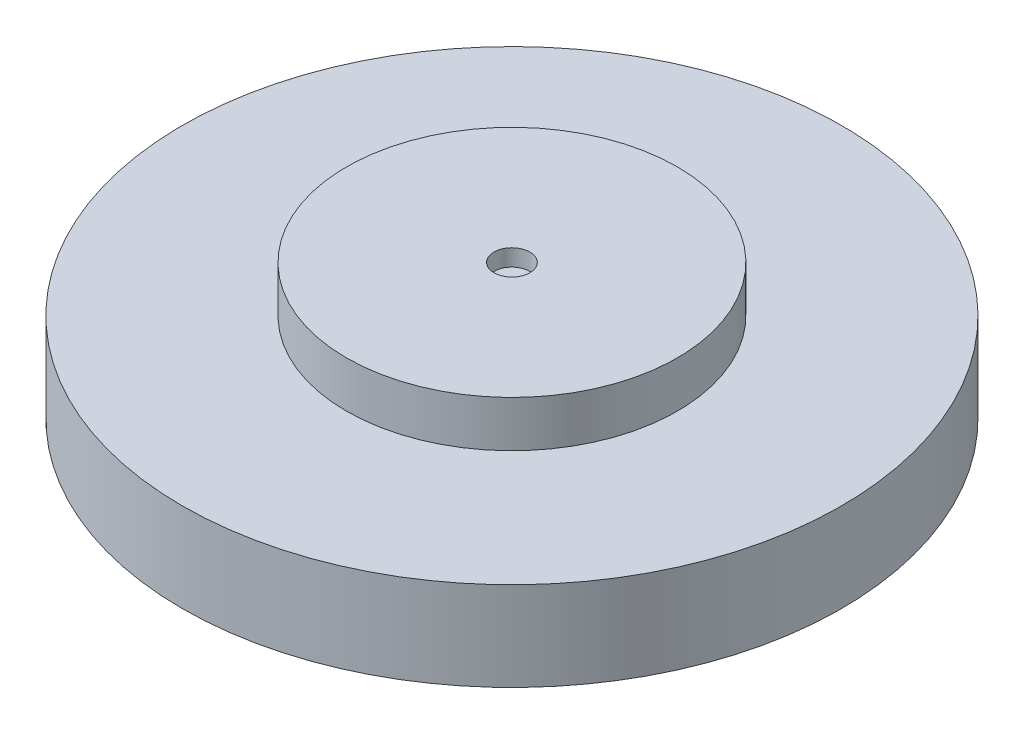
SolidWorks part; units mm, degrees
ref_plane "Front Plane" through (0, 0, 0) normal (0, 0, 1) x (1, 0, 0)
ref_plane "Top Plane" through (0, 0, 0) normal (0, 1, 0) x (1, 0, 0)
ref_plane "Right Plane" through (0, 0, 0) normal (1, 0, 0) x (0, 0, -1)
sketch "Sketch2" plane through (0, 0, 0) normal (0, 1, 0) x (1, 0, 0)
  circle A0 centre (0, 0) radius 50
  dimension "D1" = 100
extrude "Boss-Extrude1" add sketch "Sketch2" along normal blind 13.5
sketch "Sketch3" plane through (0, 13.5, 0) normal (0, 1, 0) x (1, 0, 0)
  circle A0 centre (0, 0) radius 25.1
  dimension "D1" = 50.2
extrude "Boss-Extrude2" add sketch "Sketch3" along normal blind 7
sketch "Sketch4" plane through (0, 20.5, 0) normal (0, 1, 0) x (1, 0, 0)
  circle A0 centre (0, 0) radius 2.725
  dimension "D1" = 5.45
extrude "Cut-Extrude1" cut sketch "Sketch4" against normal blind 2.55
